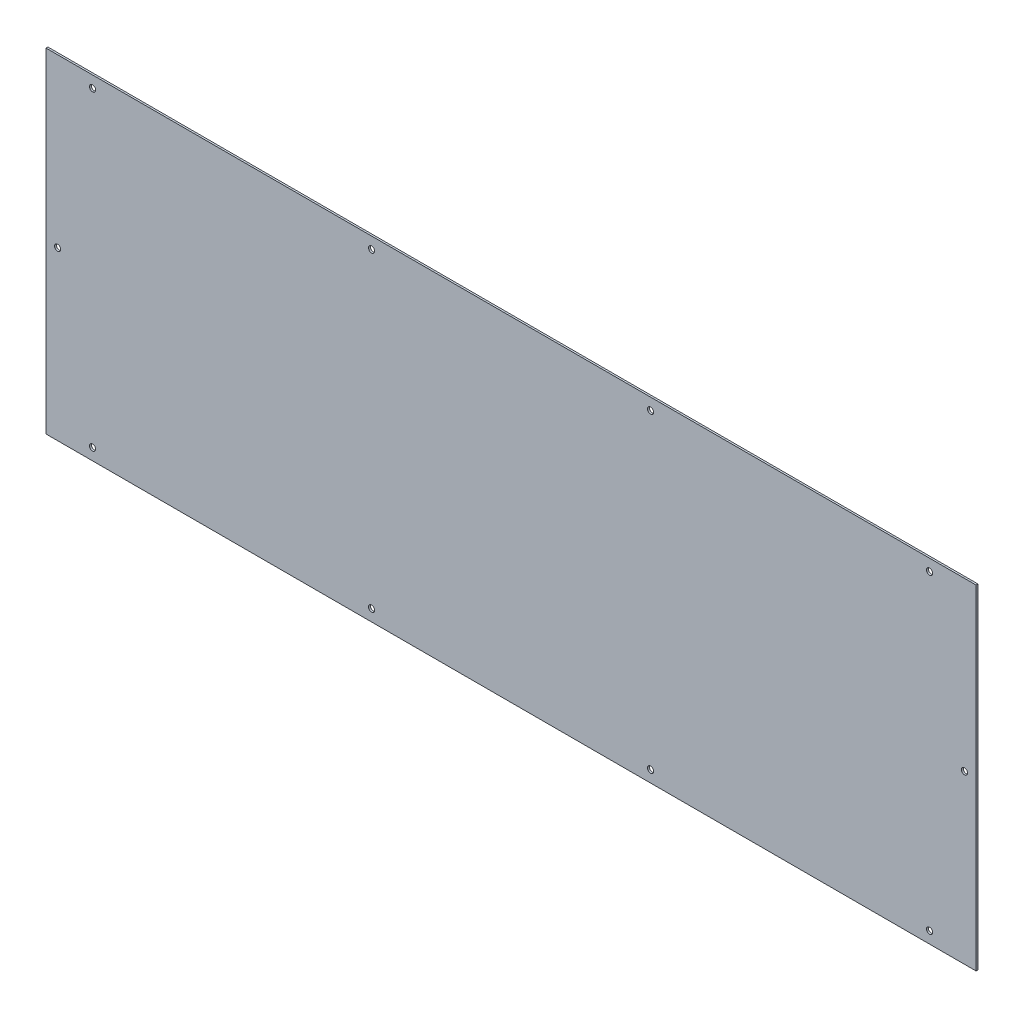
SolidWorks part; units mm, degrees
ref_plane "Front Plane" through (0, 0, 0) normal (0, 0, 1) x (1, 0, 0)
ref_plane "Top Plane" through (0, 0, 0) normal (0, 1, 0) x (1, 0, 0)
ref_plane "Right Plane" through (0, 0, 0) normal (1, 0, 0) x (0, 0, -1)
sketch "Sketch1" plane through (0, 0, 0) normal (0, 0, 1) x (1, 0, 0)
  line L1 (-499.5, -179.5) -> (499.5, -179.5)
  line L2 (-499.5, -179.5) -> (-499.5, 179.5)
  line L3 (-499.5, 179.5) -> (499.5, 179.5)
  line L4 (499.5, -179.5) -> (499.5, 179.5)
  line L5 (-499.5, -179.5) -> (499.5, 179.5) construction
  line L6 (-499.5, 179.5) -> (499.5, -179.5) construction
  point P0 (0, 0)
  dimension "D1" = 359
  dimension "D2" = 999
extrude "Boss-Extrude1" add sketch "Sketch1" along normal blind 2
hole_wizard "M6 Clearance Hole1" positions "Sketch2" profile "Sketch3" hole size "M6" standard "ISO" end condition through all
sketch "Sketch2" plane through (0, 0, 2) normal (0, 0, 1) x (1, 0, 0)
  line L0 (499.5, 179.5) -> (-499.5, 179.5) construction
  line L1 (-499.5, 179.5) -> (-499.5, -179.5) construction
  point P0 (-449.5, 167)
  dimension "D1" = 12.5
  dimension "D2" = 50
sketch "Sketch3" plane through (-449.5, 167, 2) normal (1, 0, 0) x (0, -1, 0)
  line L0 (0, 0) -> (0, 2)
  line L1 (0, 2) -> (3.3, 2)
  line L2 (3.3, 2) -> (3.3, 0)
  line L5 (3.3, 0) -> (0, 0)
  line L11 (0, -6.35) -> (0, 107.95) construction
  dimension "Thru Hole Dia." = 6.6
  dimension "Thru Hole Depth" = 2
pattern_linear "LPattern1" count 4 spacing 299.6667 along (1, 0, 0) of "M6 Clearance Hole1"
mirror "Mirror1" about plane through (0, 0, 0) normal (0, 1, 0) of "LPattern1", "M6 Clearance Hole1"
hole_wizard "M6 Clearance Hole2" positions "Sketch4" profile "Sketch5" hole size "M6" standard "ISO" end condition through all
sketch "Sketch4" plane through (0, 0, 2) normal (0, 0, 1) x (1, 0, 0)
  line L0 (-499.5, 179.5) -> (-499.5, -179.5) construction
  line L1 (-499.5, 0) -> (-487, 0) construction
  point P0 (-487, 0)
  point P5 (-499.5, 0)
  dimension "D1" = 12.5
sketch "Sketch5" plane through (-487, 0, 2) normal (1, 0, 0) x (0, -1, 0)
  line L0 (0, 0) -> (0, 2)
  line L1 (0, 2) -> (3.3, 2)
  line L2 (3.3, 2) -> (3.3, 0)
  line L5 (3.3, 0) -> (0, 0)
  line L11 (0, -6.35) -> (0, 107.95) construction
  dimension "Thru Hole Dia." = 6.6
  dimension "Thru Hole Depth" = 2
mirror "Mirror2" about plane through (0, 0, 0) normal (1, 0, 0) of "M6 Clearance Hole2"
